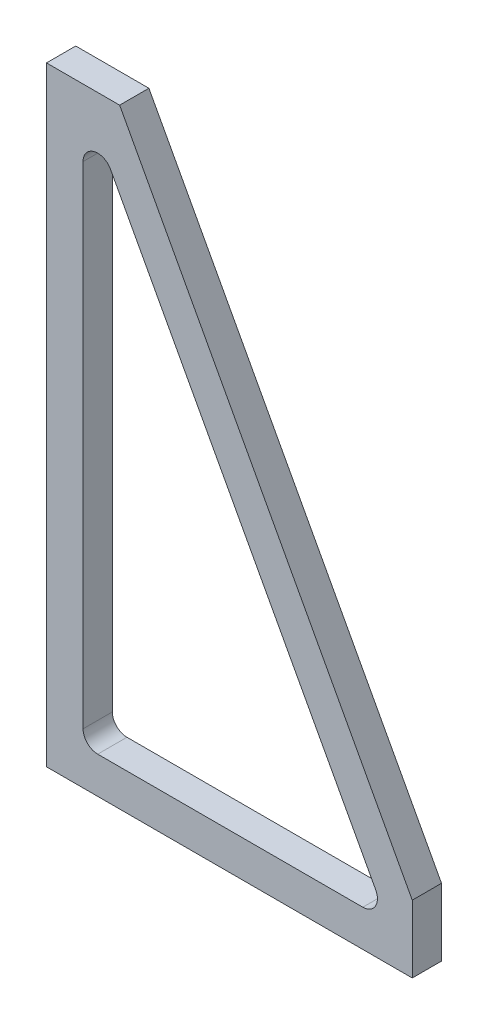
SolidWorks part; units mm, degrees
ref_plane "Front Plane" through (0, 0, 0) normal (0, 0, 1) x (1, 0, 0)
ref_plane "Top Plane" through (0, 0, 0) normal (0, 1, 0) x (1, 0, 0)
ref_plane "Right Plane" through (0, 0, 0) normal (1, 0, 0) x (0, 0, -1)
sketch "Sketch1" plane through (0, 0, 0) normal (0, 0, 1) x (1, 0, 0)
  line L10 (0, 250) -> (0, 0)
  line L11 (0, 0) -> (150, 0)
  line L12 (150, 27.6387) -> (30, 250)
  line L13 (21, 15) -> (129.7198, 15)
  line L14 (135, 23.8495) -> (26.2802, 225.3085)
  line L15 (15, 222.459) -> (15, 21)
  line L16 (0, 305.5903) -> (0, 0) construction
  line L17 (164.9156, 0) -> (0, 305.5903) construction
  line L19 (15, 15) -> (139.7757, 15) construction
  line L20 (139.7757, 15) -> (15, 246.2108) construction
  line L21 (15, 246.2108) -> (15, 15) construction
  line L22 (0, 0) -> (164.9156, 0) construction
  line L23 (150, 0) -> (150, 27.6387)
  line L24 (30, 250) -> (0, 250)
  arc A0 (129.7198, 15) -> (135, 23.8495) centre (129.7198, 21) ccw
  arc A1 (21, 15) -> (15, 21) centre (21, 21) cw
  arc A2 (26.2802, 225.3085) -> (15, 222.459) centre (21, 222.459) ccw
  point P7 (0, 305.5903)
  point P8 (0, 251.7913)
  point P9 (0, 250.585)
  point P19 (0, 0)
  point P20 (0, 0)
  dimension "D7" = 250
  dimension "D2" = 6
  dimension "D3" = 6
  dimension "D1" = 15
  dimension "D4" = 30
  dimension "D5" = 90
  dimension "D6" = 90
  dimension "D8" = 150
  dimension "D9" = 15
extrude "Boss-Extrude2" add sketch "Sketch1" along normal blind 12
